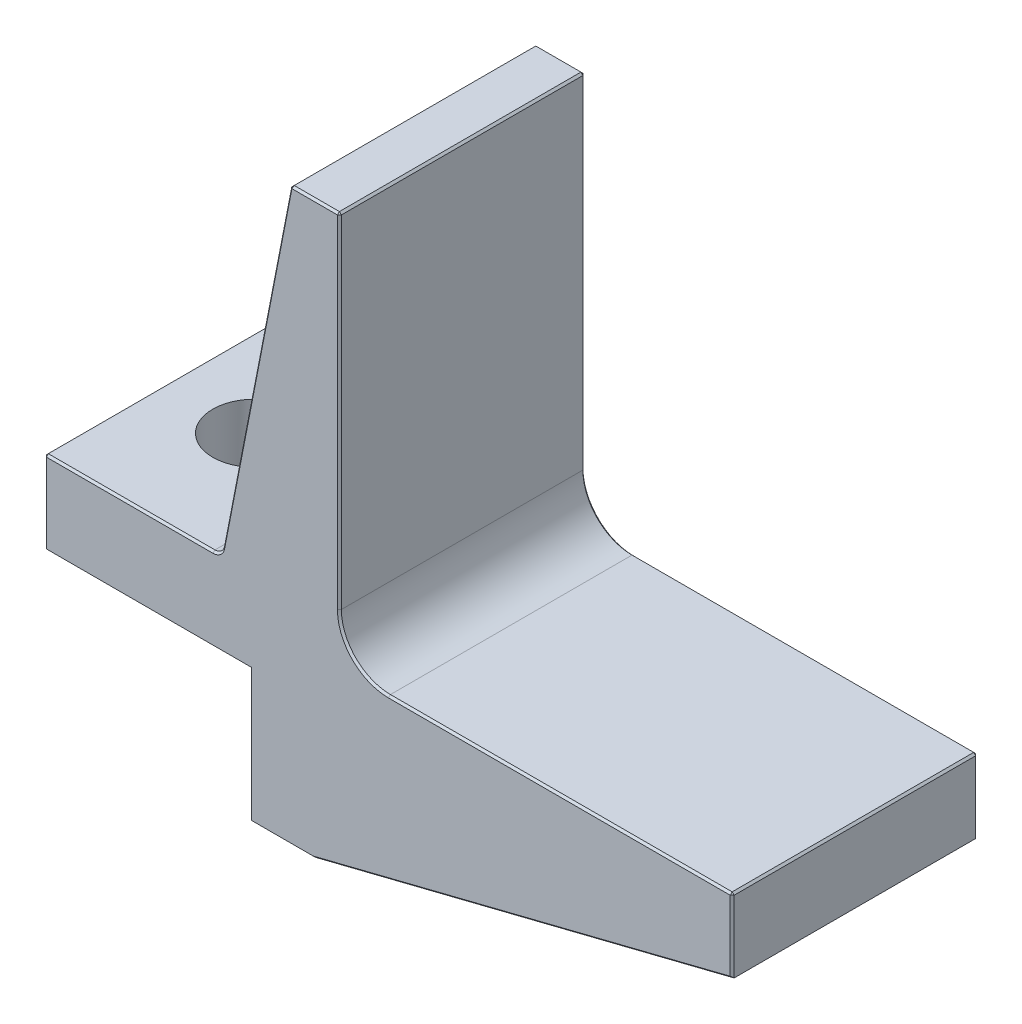
SolidWorks part; units mm, degrees
other "Markup1"
sketch "Sketch7" plane through (-38.1608, 50.8, 31.75) normal (-0.1424, 0.1459, 0.979) x (0.9898, 0.0098, 0.1425)
material "7075-T6 (SN)"
ref_plane "Front Plane" through (0, 0, 0) normal (0, 0, 1) x (1, 0, 0)
ref_plane "Top Plane" through (0, 0, 0) normal (0, 1, 0) x (1, 0, 0)
ref_plane "Right Plane" through (0, 0, 0) normal (1, 0, 0) x (0, 0, -1)
sketch "Sketch1" plane through (0, 0, 0) normal (0, 0, 1) x (1, 0, 0)
  line L0 (0, 0) -> (50.8, 0)
  line L1 (50.8, 0) -> (50.8, -9.525)
  line L2 (-11.6178, -5.9413) -> (-38.1608, -5.9413)
  line L3 (-38.1608, -5.9413) -> (-38.1608, 4.8537)
  line L4 (-38.1608, 4.8537) -> (-15.3008, 4.8537)
  line L5 (-15.3008, 4.8537) -> (-6.35, 50.8)
  line L6 (-6.35, 50.8) -> (0, 50.8)
  line L7 (0, 50.8) -> (0, 0)
  line L8 (-11.6178, -5.9413) -> (-11.6178, -23.0863)
  line L9 (-11.6178, -23.0863) -> (-3.3628, -23.0863)
  line L10 (-3.3628, -23.0863) -> (50.8, -9.525)
  dimension "D1" = 50.8
  dimension "D2" = 50.8
  dimension "D3" = 9.525
  dimension "D4" = 38.1608
  dimension "D5" = 6.35
  dimension "D6" = 22.86
  dimension "D7" = 26.543
  dimension "D8" = 10.795
  dimension "D9" = 17.145
  dimension "D10" = 8.255
  dimension "D11" = 4.8537
extrude "Boss-Extrude1" add sketch "Sketch1" along normal blind 31.75
hole_wizard "3/8 (0.375) Diameter Hole1" positions "Sketch8" profile "Sketch3" hole size "3/8" standard "ANSI Inch" end condition through all
sketch "Sketch8" plane through (0, 4.8537, 0) normal (0, 1, 0) x (1, 0, 0)
  line L1 (-38.1608, -31.75) -> (-38.1608, 0) construction
  point P0 (-26.8578, -15.875)
  point P8 (-38.1608, -15.875)
  dimension "D1" = 11.303
sketch "Sketch3" plane through (-26.8578, 4.8537, 15.875) normal (1, 0, 0) x (0, 0, 1)
  line L0 (0, 0) -> (0, 27.94)
  line L1 (0, 27.94) -> (5.3975, 27.94)
  line L2 (5.3975, 27.94) -> (5.3975, 0)
  line L5 (5.3975, 0) -> (0, 0)
  line L11 (0, -6.35) -> (0, 107.95) construction
  dimension "Thru Hole Dia." = 10.795
  dimension "Thru Hole Depth" = 27.94
fillet "Fillet1" radius 1.27 1 edges at (-15.3008, 4.8537, 15.875)
fillet "Fillet2" radius 6.35 1 edges at (0, 0, 15.875)
chamfer "Chamfer1" distance 0.254 angle 45 31 edges at (-6.35, 50.8, 15.875) (-3.175, 50.8, 0) (-10.7254, 28.3404, 0) (-15.5397, 5.1436, 0) (-27.254, 4.8537, 0) (-38.1608, -0.5438, 0) (-24.8893, -5.9413, 0) (50.8, -4.7625, 0) (28.575, 0, 0) (1.8599, 1.8599, 0) (0, 28.575, 0) (50.8, -4.7625, 31.75) (-24.8893, -5.9413, 31.75) (-38.1608, -5.9413, 15.875) (-38.1608, -0.5438, 31.75) (-38.1608, 4.8537, 15.875) (-27.254, 4.8537, 31.75) (-15.5397, 5.1436, 31.75) (-10.7254, 28.3404, 31.75) (-3.175, 50.8, 31.75) (0, 50.8, 15.875) (0, 28.575, 31.75) (1.8599, 1.8599, 31.75) (28.575, 0, 31.75) (50.8, 0, 15.875) (-11.6178, -14.5138, 0) (-7.4903, -23.0863, 0) (23.7186, -16.3057, 0) (23.7186, -16.3057, 31.75) (-7.4903, -23.0863, 31.75) (-11.6178, -14.5138, 31.75)
